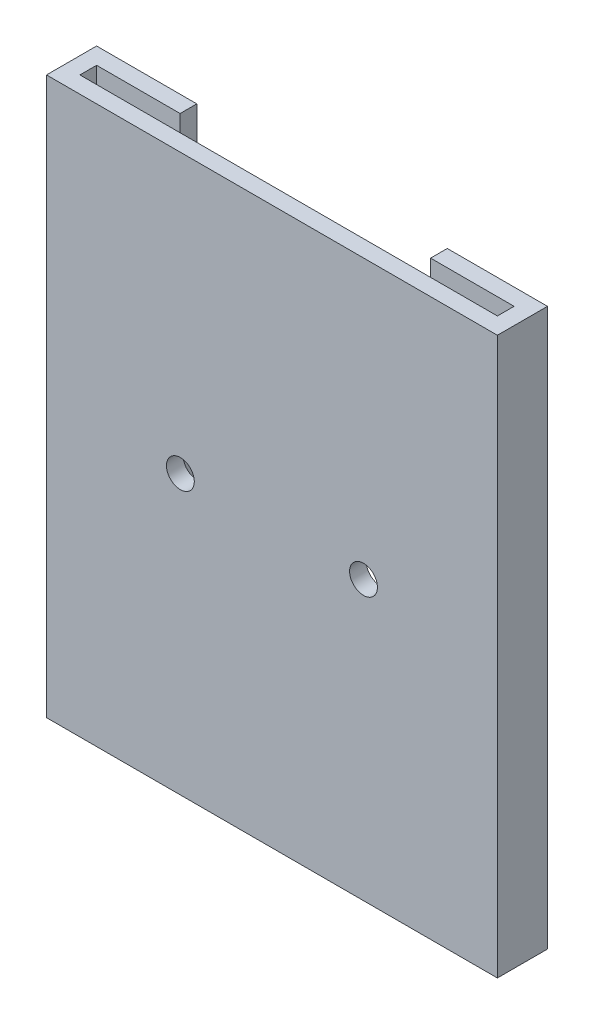
SolidWorks part; units mm, degrees
ref_plane "Front Plane" through (0, 0, 0) normal (0, 0, 1) x (1, 0, 0)
ref_plane "Top Plane" through (0, 0, 0) normal (0, 1, 0) x (1, 0, 0)
ref_plane "Right Plane" through (0, 0, 0) normal (1, 0, 0) x (0, 0, -1)
sketch "Sketch1" plane through (0, 0, 0) normal (0, 1, 0) x (1, 0, 0)
  line L0 (-12.1748, 0) -> (17.8252, 0)
  line L1 (17.8252, 0) -> (17.8252, -6)
  line L2 (17.8252, -6) -> (-132.1748, -6)
  line L3 (-132.1748, -6) -> (-132.1748, 0)
  line L4 (-57.1748, 60.2705) -> (-57.1748, -59.5459) construction
  line L5 (-12.1748, 0) -> (-12.1748, 6)
  line L6 (-12.1748, 6) -> (23.8252, 6)
  line L7 (23.8252, 6) -> (23.8252, -12)
  line L8 (23.8252, -12) -> (-138.1748, -12)
  line L9 (-138.1748, 6) -> (-138.1748, -12)
  line L10 (-102.1748, 6) -> (-138.1748, 6)
  line L11 (-102.1748, 0) -> (-102.1748, 6)
  line L13 (-102.1748, 0) -> (-132.1748, 0)
  point P13 (-57.1748, -6)
  point P14 (-57.1748, -12)
  dimension "D1" = 6
  dimension "D2" = 150
  dimension "D3" = 30
  dimension "D4" = 18
  dimension "D5" = 12
extrude "Boss-Extrude1" add sketch "Sketch1" along normal blind 200
sketch "Sketch2" plane through (0, 0, 6) normal (0, 0, -1) x (-1, 0, 0)
  line L0 (57.1748, 200) -> (57.1748, 0) construction
  line L1 (-17.8252, 200) -> (132.1748, 200) construction
  line L2 (-17.8252, 0) -> (132.1748, 0) construction
  line L3 (-23.8252, 100) -> (138.1748, 100) construction
  line L4 (-23.8252, 200) -> (-23.8252, 0) construction
  line L5 (138.1748, 200) -> (138.1748, 0) construction
  circle A0 centre (24.2748, 100) radius 5
  circle A1 centre (90.0748, 100) radius 5
  dimension "D2" = 48.1
  dimension "D1" = 100
extrude "Cut-Extrude1" cut sketch "Sketch2" against normal through all
